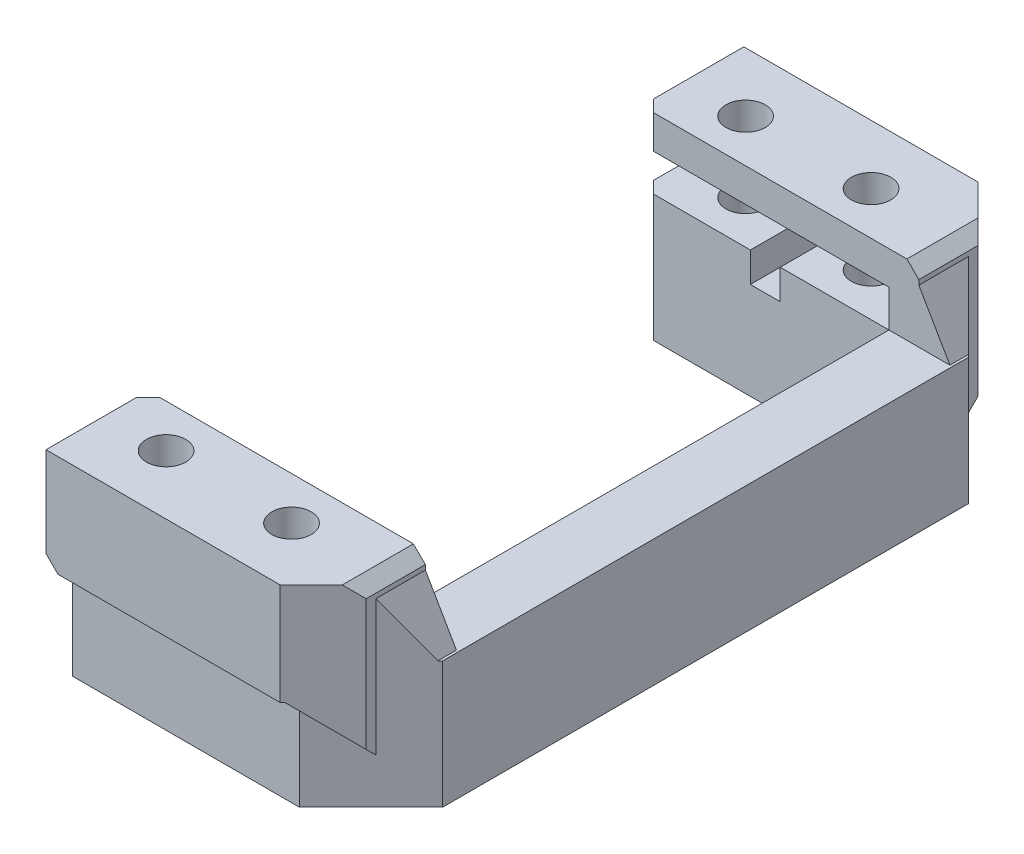
SolidWorks part; units mm, degrees
ref_plane "前视基准面" through (0, 0, 0) normal (0, 0, 1) x (1, 0, 0)
ref_plane "上视基准面" through (0, 0, 0) normal (0, 1, 0) x (1, 0, 0)
ref_plane "右视基准面" through (0, 0, 0) normal (1, 0, 0) x (0, 0, -1)
sketch "草图1" plane through (0, 0, 0) normal (0, 1, 0) x (1, 0, 0)
  line L1 (-13, 28) -> (13, 28)
  line L2 (-13, 28) -> (-13, -28)
  line L3 (-13, -28) -> (13, -28)
  line L4 (13, 28) -> (13, -28)
  line L5 (-13, 28) -> (13, -28) construction
  line L6 (-13, -28) -> (13, 28) construction
  point P0 (0, 0)
  dimension "D1" = 56
  dimension "D2" = 26
extrude "凸台-拉伸1" add sketch "草图1" along normal blind 10.61
sketch "草图2" plane through (0, 10.61, 0) normal (0, 1, 0) x (1, 0, 0)
  line L0 (-13, 28) -> (-13, -28) construction
  line L1 (7.7, 20.65) -> (-13, 20.65)
  line L2 (7.7, 20.65) -> (7.7, -20.65)
  line L3 (7.7, -20.65) -> (-13, -20.65)
  line L4 (-13, 20.65) -> (-13, -20.65)
  line L5 (7.7, 20.65) -> (-13, -20.65) construction
  line L6 (7.7, -20.65) -> (-13, 20.65) construction
  line L7 (13, 0) -> (-13, 0) construction
  line L8 (13, -28) -> (13, 28) construction
  line L9 (-2.65, 20.65) -> (-2.65, -20.65) construction
  circle A0 centre (-7.9, 24.25) radius 1.65
  circle A1 centre (2.6, 24.25) radius 1.65
  circle A2 centre (2.6, -24.25) radius 1.65
  circle A3 centre (-7.9, -24.25) radius 1.65
  point P0 (-2.65, 0)
  dimension "D3" = 3.3
  dimension "D1" = 41.3
  dimension "D2" = 20.7
  dimension "D4" = 3.6
  dimension "D5" = 5.1
extrude "切除-拉伸1" cut sketch "草图2" against normal through all
sketch "草图3" plane through (0, 10.61, 0) normal (0, 1, 0) x (1, 0, 0)
  line L0 (-2.65, 20.65) -> (-2.65, -20.65) construction
  line L1 (7.7, 20.65) -> (-13, 20.65) construction
  line L2 (-13, -20.65) -> (7.7, -20.65) construction
  line L4 (-3.9, 28) -> (-1.4, 28)
  line L5 (-3.9, 28) -> (-3.9, -28)
  line L6 (-3.9, -28) -> (-1.4, -28)
  line L7 (-1.4, 28) -> (-1.4, -28)
  line L9 (13, 28) -> (-13, 28) construction
  point P10 (-5.3, 28)
  point P12 (-1.2063, 28)
  dimension "D1" = 2.5
extrude "切除-拉伸2" cut sketch "草图3" against normal blind 2.5
sketch "草图4" plane through (0, 0, -20.65) normal (0, 0, 1) x (1, 0, 0)
  line L0 (-13, 0) -> (-13, 10.61) construction
  line L1 (-13, 16.51) -> (10.2, 16.51)
  line L2 (-13, 16.51) -> (-13, 13.71)
  line L3 (-13, 13.71) -> (10.2, 13.71)
  line L4 (10.2, 16.51) -> (10.2, 13.71)
  line L5 (7.7, 0) -> (7.7, 10.61) construction
  line L6 (-3.9, 10.61) -> (-13, 10.61) construction
  line L7 (7.7, 10.61) -> (-1.4, 10.61) construction
  line L8 (7.7, 13.71) -> (10.2, 13.71)
  line L9 (7.7, 13.71) -> (7.7, 10.61)
  line L10 (7.7, 10.61) -> (10.2, 10.61)
  line L11 (10.2, 13.71) -> (10.2, 10.61)
  dimension "D1" = 2.5
  dimension "D2" = 3.1
  dimension "D3" = 2.8
extrude "凸台-拉伸2" add sketch "草图4" against normal blind 7.35 contours L4 L1 L2 L3 | L11 L3 L9 L10
sketch "草图5" plane through (0, 0, -28) normal (0, 0, -1) x (-1, 0, 0)
  line L0 (13, 10.61) -> (13, 0) construction
  line L1 (-10.2, 16.51) -> (13, 16.51)
  line L2 (-10.2, 16.51) -> (-10.2, 7.9826)
  line L3 (-10.2, 7.9826) -> (13, 7.9826)
  line L4 (13, 16.51) -> (13, 7.9826)
extrude "凸台-拉伸5" add sketch "草图5" along normal blind 1.2
sketch "草图6" plane through (0, 16.51, 0) normal (0, 1, 0) x (1, 0, 0)
  circle A0 centre (2.6, 24.25) radius 1.65 construction
  circle A1 centre (-7.9, 24.25) radius 1.65 construction
  circle A2 centre (2.6, 24.25) radius 1.65
  circle A3 centre (-7.9, 24.25) radius 1.65
extrude "切除-拉伸3" cut sketch "草图6" against normal through all
mirror "镜向2" about plane through (0, 0, 0) normal (0, 0, 1) of "凸台-拉伸2", "凸台-拉伸5", "切除-拉伸3"
chamfer "倒角1" distance 4.5 angle 30 2 edges at (10.2, 10.61, 24.325) (10.2, 10.61, -24.325)
chamfer "倒角2" distance 1 angle 45 12 edges at (-13, 3.9913, -28) (-1.4, 7.9826, -28) (-13, 7.9826, -28.6) (10.2, 16.51, 24.925) (-13, 15.11, 20.65) (-13, 3.9913, 28) (-1.4, 7.9826, 28) (-13, 7.9826, 28.6) (-13, 5.305, 20.65) (-13, 5.305, -20.65) (10.2, 16.51, -24.925) (-13, 15.11, -20.65)
chamfer "倒角3" distance 6 angle 45 2 edges at (13, 5.305, 28) (13, 5.305, -28)
chamfer "倒角6" distance 3.6 angle 45 2 edges at (10.2, 11.7463, 29.2) (10.2, 11.7463, -29.2)
